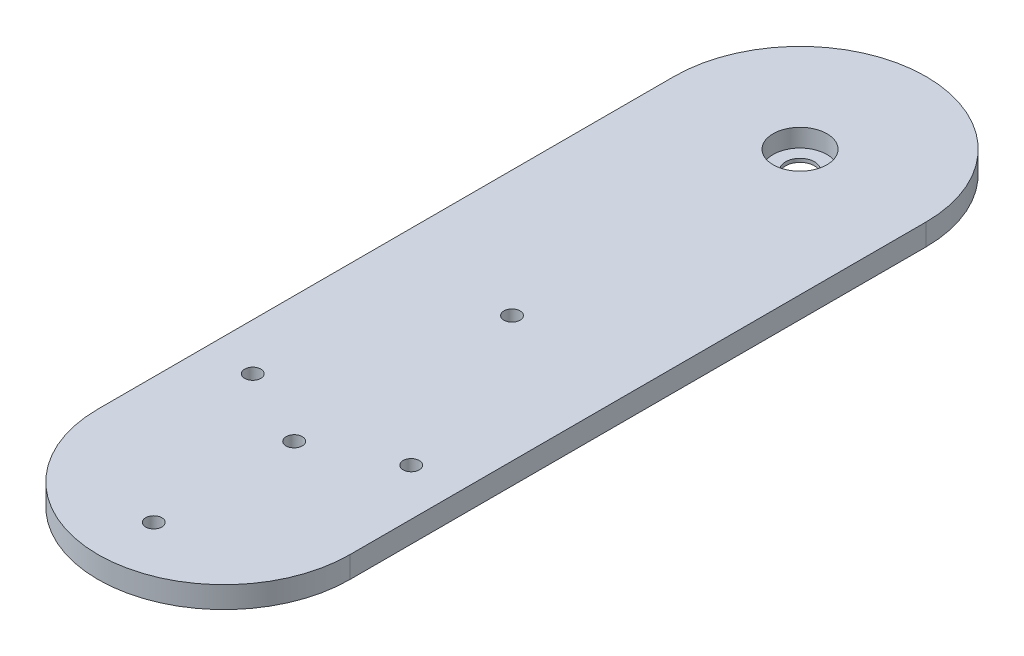
SolidWorks part; units mm, degrees
material "Aleación 6061"
ref_plane "Alzado" through (0, 0, 0) normal (0, 0, 1) x (1, 0, 0)
ref_plane "Planta" through (0, 0, 0) normal (0, 1, 0) x (1, 0, 0)
ref_plane "Vista lateral" through (0, 0, 0) normal (1, 0, 0) x (0, 0, -1)
sketch "Sk_Placa" plane through (0, 0, 0) normal (0, 1, 0) x (1, 0, 0)
  line L1 (-35, -330) -> (35, -330)
  line L2 (-35, -330) -> (-35, -170)
  line L3 (-35, -170) -> (35, -170)
  line L4 (35, -330) -> (35, -170)
  line L5 (-35, -330) -> (35, -170) construction
  line L6 (-35, -170) -> (35, -330) construction
  point P0 (0, -250)
  dimension "D1" = 70
  dimension "D2" = 160
  dimension "D3" = 250
extrude "Placa" add sketch "Sk_Placa" along normal blind 6 from offset 52.75
sketch "Sk_Extremos" plane through (0, 0, 0) normal (0, 1, 0) x (1, 0, 0)
  circle A0 centre (0, -170) radius 35
  circle A1 centre (0, -330) radius 35
  dimension "D1" = 70
  dimension "D3" = 70
  dimension "D2" = 170
  dimension "D4" = 330
extrude "Extremos" add sketch "Sk_Extremos" along normal blind 6 from offset 52.75
sketch "Sk_Pasantes_M4_separadores" plane through (0, 0, 0) normal (0, 1, 0) x (1, 0, 0)
  circle A0 centre (0, -250) radius 2.25
  circle A1 centre (-22, -300) radius 2.25
  circle A2 centre (22, -300) radius 2.25
  dimension "D1" = 4.5
  dimension "D3" = 4.5
  dimension "D6" = 4.5
  dimension "D2" = 250
  dimension "D4" = 22
  dimension "D5" = 300
  dimension "D7" = 22
  dimension "D8" = 300
extrude "Pasantes_M4_separadores" cut sketch "Sk_Pasantes_M4_separadores" along normal blind 6 from offset 52.75
sketch "Sk_Alojamiento_696ZZ" plane through (0, 0, 0) normal (0, 1, 0) x (1, 0, 0)
  circle A0 centre (0, -170) radius 7.475
  dimension "D1" = 14.95
  dimension "D2" = 170
extrude "Alojamiento_696ZZ" cut sketch "Sk_Alojamiento_696ZZ" along normal blind 5 from offset 51.75
sketch "Sk_Paso_extractor" plane through (0, 0, 0) normal (0, 1, 0) x (1, 0, 0)
  circle A0 centre (0, -170) radius 4
  dimension "D1" = 8
  dimension "D2" = 170
extrude "Paso_extractor" cut sketch "Sk_Paso_extractor" along normal blind 1 from offset 52.75
sketch "Sk_Pasantes_M4_ejefalso_J3" plane through (0, 0, 0) normal (0, 1, 0) x (1, 0, 0)
  circle A0 centre (0, -310.5) radius 2.25
  circle A1 centre (0, -349.5) radius 2.25
  dimension "D1" = 4.5
  dimension "D3" = 4.5
  dimension "D2" = 310.5
  dimension "D4" = 349.5
extrude "Pasantes_M4_ejefalso_J3" cut sketch "Sk_Pasantes_M4_ejefalso_J3" along normal blind 6 from offset 52.75
